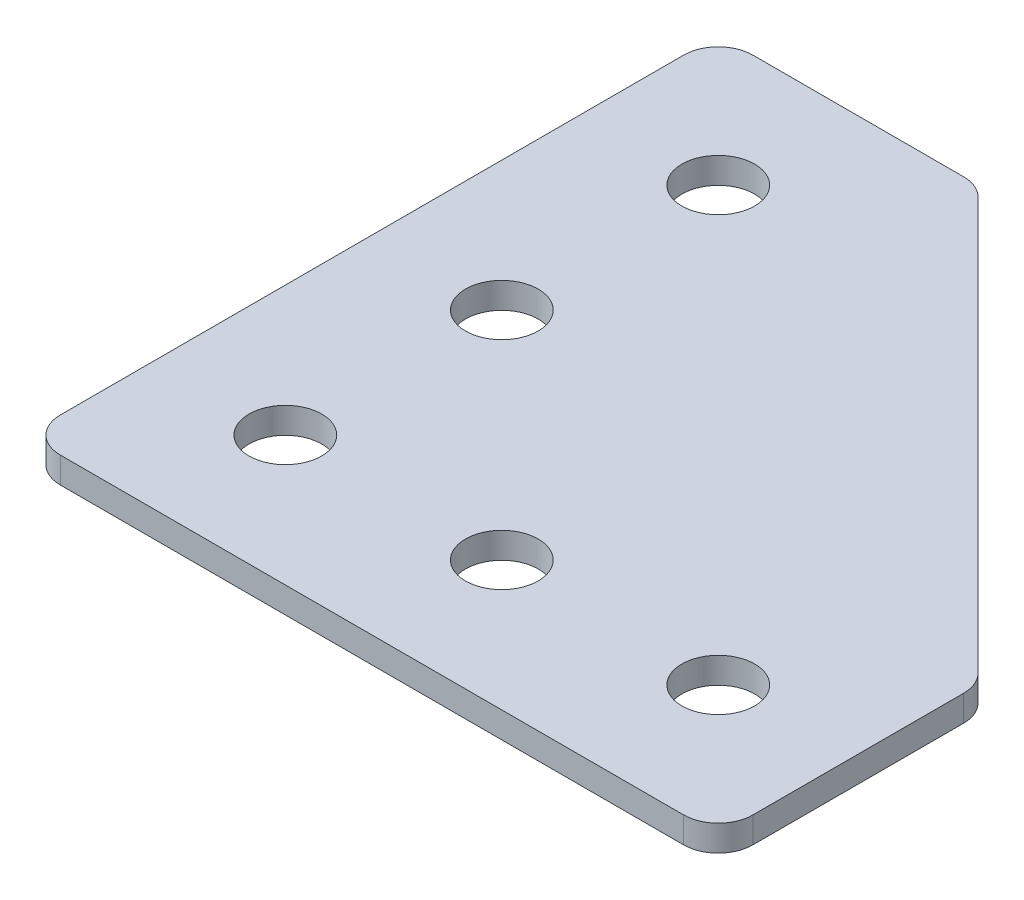
SolidWorks part; units mm, degrees
material "1060 合金"
ref_plane "正面" through (0, 0, 0) normal (0, 0, 1) x (1, 0, 0)
ref_plane "平面" through (0, 0, 0) normal (0, 1, 0) x (1, 0, 0)
ref_plane "右側面" through (0, 0, 0) normal (1, 0, 0) x (0, 0, -1)
sketch "ｽｹｯﾁ2" plane through (0, 0, 0) normal (0, 1, 0) x (1, 0, 0)
  line L0 (0, 0) -> (40, 0)
  line L1 (40, 0) -> (40, 15)
  line L2 (40, 15) -> (15, 40)
  line L3 (15, 40) -> (0, 40)
  line L4 (0, 40) -> (0, 0)
  line L5 (0, 0) -> (27.5, 27.5) construction
  line L6 (40, 7.5) -> (0, 7.5) construction
  circle A0 centre (7.5, 7.5) radius 2.1
  circle A1 centre (32.5, 7.5) radius 2.1
  circle A2 centre (7.5, 32.5) radius 2.1
  circle A3 centre (20, 7.5) radius 2.1
  circle A4 centre (7.5, 20) radius 2.1
  dimension "D1" = 15
  dimension "D2" = 4.2
  dimension "D3" = 7.5
  dimension "D4" = 7.5
  dimension "D5" = 25
  dimension "D6" = 12.5
  dimension "D7" = 12.5
extrude "ﾎﾞｽ - 押し出し1" add sketch "ｽｹｯﾁ2" along normal blind 1.5
fillet "ﾌｨﾚｯﾄ1" radius 2 5 edges at (0, 0.75, 0) (40, 0.75, 0) (40, 0.75, -15) (15, 0.75, -40) (0, 0.75, -40)
